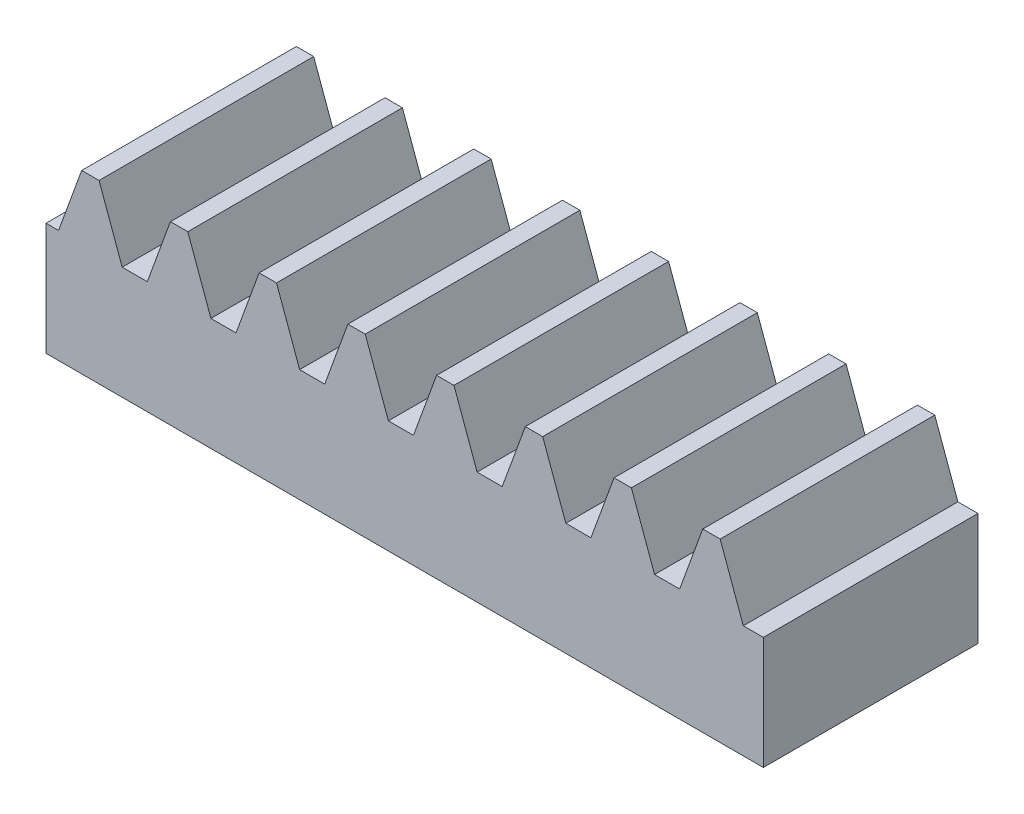
SolidWorks part; units mm, degrees
extrude "Blank" add sketch "BlankSke" against normal blind 3.8
sketch "BlankSke" plane through (0, 0, 0) normal (0, 0, 1) x (1, 0, 0)
  line L1 (0, 0) -> (12.7, 0)
  line L2 (0, 0) -> (0, 3.12)
  line L3 (0, 3.12) -> (12.7, 3.12)
  line L4 (12.7, 0) -> (12.7, 3.12)
  dimension "Length" = 12.7
  dimension "Blank_height" = 3.12
ref_plane "Plane1" through (0, 0, 0) normal (0, 0, 1) x (1, 0, 0)
ref_plane "Plane2" through (0, 0, 0) normal (0, 1, 0) x (1, 0, 0)
ref_plane "Plane3" through (0, 0, 0) normal (1, 0, 0) x (0, 0, -1)
other "Configuration Table"
sketch "HoldingSke" plane through (0, 0, 0) normal (0, 1, 0) x (1, 0, 0)
  line L0 (0, 0) -> (0.2783, 1.9805)
  line L1 (-15, 0) -> (100, 0) construction
  line L2 (0, 0) -> (-2.1039, 2.3779)
  line L3 (0, 0) -> (-11.863, 4.5341)
  line L4 (0, 0) -> (8.5048, 1.4996)
  line L5 (0, 0) -> (-23.7986, -8.8762)
  line L6 (0, 0) -> (-10.5278, -7.1032)
  line L9 (-71.009, 38.7566) -> (-59.0749, 43.1003)
  line L10 (-76.2, 2.8779) -> (-73.58, 2.8779)
  line L11 (0, 0) -> (-3.8, 0)
  line L12 (-76.2, 101.6) -> (-76.181, 101.6)
  line L13 (24.9733, 27.94) -> (52.9518, 28.4284)
  line L14 (24.9733, 27.94) -> (24.9743, 27.94)
  line L15 (24.9733, 27.94) -> (100.4006, 29.5858)
  circle A0 centre (0, 0) radius 19.05
  circle A1 centre (0, 0) radius 1.31
  circle A2 centre (0, 0) radius 12.7
  dimension "MPH" = 2.62
  dimension "Diameter" = 38.1
  dimension "Num_teeth" = 10
  dimension "Pitch" = 2
  dimension "Show_teeth" = 998
  dimension "Thickness" = 12.7
  dimension "Ap" = 20
  dimension "Pitch_height" = 2.62
  dimension "Width" = 3.8
  dimension "Backlash" = 0.019
  dimension "Addendum_fac" = 1
  dimension "Dedendum_fac" = 1.25
  dimension "Clearance_fac" = 0.25
  dimension "Dedendum_add" = 0.001
  dimension "Length" = 12.7
  dimension "Module" = 0.5
sketch "TooCutSkeIll" plane through (0, 0, 0) normal (0, 0, 1) x (1, 0, 0)
  line L0 (-0.6269, 3.1068) -> (-0.2524, 2.0779)
  line L1 (-0.134, 1.995) -> (0.134, 1.995)
  line L2 (0.2524, 2.0779) -> (0.6269, 3.1068)
  line L3 (12.7, 3.12) -> (0, 3.12) construction
  line L4 (0, 0) -> (0, 64.897) construction
  line L5 (-13.208, 2.62) -> (12.954, 2.62) construction
  line L6 (0, 0) -> (12.7, 0) construction
  line L7 (0.4497, 2.62) -> (0.4497, 48.7463) construction
  line L8 (-0.4497, 2.62) -> (-0.4497, 48.7463) construction
  line L9 (0.6457, 3.12) -> (0.6457, 3.1454)
  line L10 (-0.6457, 3.12) -> (-0.6457, 3.1454)
  line L11 (-0.6457, 3.1454) -> (0.6457, 3.1454)
  arc A0 (0.134, 1.995) -> (0.2524, 2.0779) centre (0.134, 2.121) ccw
  arc A1 (-0.2524, 2.0779) -> (-0.134, 1.995) centre (-0.134, 2.121) ccw
  arc A2 (0.6457, 3.12) -> (0.6269, 3.1068) centre (0.6457, 3.1) ccw
  arc A3 (-0.6269, 3.1068) -> (-0.6457, 3.12) centre (-0.6457, 3.1) ccw
  dimension "Pitch_height" = 2.62
  dimension "Addendum_plus" = 0.5254
  dimension "Pressure_angle" = 20
  dimension "Gap_width" = 0.8994
  dimension "Dedendum" = 0.625
extrude "ToothCutIll" [suppressed] cut sketch "TooCutSkeIll" against normal through all
sketch "TooCutSkeSim" plane through (0, 0, 0) normal (0, 0, 1) x (1, 0, 0)
  line L0 (0.2222, 1.995) -> (-0.2222, 1.995)
  line L1 (0.6409, 3.1454) -> (0.2222, 1.995)
  line L2 (0, 17.4625) -> (0, 53.467) construction
  line L3 (0.6409, 3.1454) -> (-0.6409, 3.1454)
  line L6 (-0.6409, 3.1454) -> (-0.2222, 1.995)
  line L9 (-0.4497, 2.62) -> (0.4497, 2.62) construction
  line L10 (0, 0) -> (12.7, 0) construction
  line L11 (0.4497, 2.62) -> (0.4497, 53.467) construction
  line L12 (-0.4497, 2.62) -> (-0.4497, 53.467) construction
  dimension "Pitch_height" = 2.62
  dimension "Addendum_plus" = 0.5254
  dimension "Pressure_angle" = 20
  dimension "Gap_width" = 0.8994
  dimension "Dedendum" = 0.625
extrude "ToothCutSim" cut sketch "TooCutSkeSim" against normal through all
pattern_linear "TeethCuts" count 9 spacing 1.5708 along (1, 0, 0) of "ToothCutIll", "ToothCutSim"
equation "' \"Module@HoldingSke\" = 6.35"
equation "' \"Num_teeth@HoldingSke\" = 12"
equation "' \"Ap@HoldingSke\" =  20"
equation "' \"Ap@HoldingSke\" = 20"
equation "' \"Width@HoldingSke\" = 0.25 * 25.4"
equation "' \"Show_teeth@HoldingSke\" = 500"
equation "' \"Backlash@HoldingSke\" = 0.009 * 25.4"
equation "' \"Addendum_fac@HoldingSke\" = 1.0"
equation "' \"Dedendum_fac@HoldingSke\" = 1.25"
equation "' \"Dedendum_add@HoldingSke\" = 0.00005 * 25.4"
equation "' \"Clearance_fac@HoldingSke\" = 0.25"
equation "' \"Pitch_height@HoldingSke\" = 1 * 25.4"
equation "' \"Length@HoldingSke\" = 4.71 * 25.4"
equation "\"Pitch@HoldingSke\" = 1 / \"Module@HoldingSke\""
equation "\"MPH@HoldingSke\" = \"Dedendum_fac@HoldingSke\" / \"Pitch@HoldingSke\" + 2 * \"Dedendum_add@HoldingSke\" + 0.002 * 25.4"
equation "\"MPH@HoldingSke\" = ((sgn( \"MPH@HoldingSke\" - \"Pitch_height@HoldingSke\")+1)*( \"MPH@HoldingSke\" - \"Pitch_height@HoldingSke\"))/2 + \"Pitch_height@HoldingSke\""
equation "\"Blank_height@BlankSke\" = \"Pitch_height@HoldingSke\" + \"Addendum_fac@HoldingSke\"  / \"Pitch@HoldingSke\" "
equation "\"Length@BlankSke\" =  \"Length@HoldingSke\""
equation "\"Face_width@Blank\" = \"Width@HoldingSke\""
equation "\"Pressure_angle@TooCutSkeIll\" = \"Ap@HoldingSke\""
equation "\"Addendum_plus@TooCutSkeIll\" =  \"Addendum_fac@HoldingSke\"  / \"Pitch@HoldingSke\" + 0.001 *25.4"
equation "\"Dedendum@TooCutSkeIll\" = \"Dedendum_fac@HoldingSke\"  / \"Pitch@HoldingSke\""
equation "\"Pitch_height@TooCutSkeIll\" =  \"MPH@HoldingSke\""
equation "\"Gap_width@TooCutSkeIll\" = 3.14159265 / 2 / \"Pitch@HoldingSke\" + 6 * \"Backlash@HoldingSke\""
equation "\"Pressure_angle@TooCutSkeSim\" = \"Ap@HoldingSke\""
equation "\"Addendum_plus@TooCutSkeSim\" =  \"Addendum_fac@HoldingSke\"  / \"Pitch@HoldingSke\" + 0.001 * 25.4"
equation "\"Dedendum@TooCutSkeSim\" = \"Dedendum_fac@HoldingSke\"  / \"Pitch@HoldingSke\""
equation "\"Pitch_height@TooCutSkeSim\" =  \"MPH@HoldingSke\""
equation "\"Gap_width@TooCutSkeSim\" = 3.14159265 / 2 / \"Pitch@HoldingSke\" + 6 * \"Backlash@HoldingSke\""
equation "\"Root_fillet@TooCutSkeIll\" = \"Clearance_fac@HoldingSke\" / \"Pitch@HoldingSke\" + \"Dedendum_add@HoldingSke\""
equation "\"Break_rad@TooCutSkeIll\" = 0.02 / \"Pitch@HoldingSke\" * 2"
equation "\"Linear_pitch@TeethCuts\" = 3.14159265 / \"Pitch@HoldingSke\""
equation "\"Num_teeth@HoldingSke\" = int( ( \"Length@HoldingSke\" + 0 ) / (3.14159265 / \"Pitch@HoldingSke\")) + 0.9999  + 1"
equation " \"Num_teeth@TeethCuts\" = int( \"Show_teeth@HoldingSke\" ) + 1"
equation " \"Num_teeth@TeethCuts\" = ((sgn( \"Num_teeth@TeethCuts\" - \"Num_teeth@HoldingSke\" )-1)*( \"Num_teeth@TeethCuts\" - \"Num_teeth@HoldingSke\" ))/-2+ \"Num_teeth@HoldingSke\""
equation " \"Num_teeth@TeethCuts\" = ((sgn( \"Num_teeth@TeethCuts\" - 2.0)+1)*( \"Num_teeth@TeethCuts\" - 2.0))/2 +2.0"
